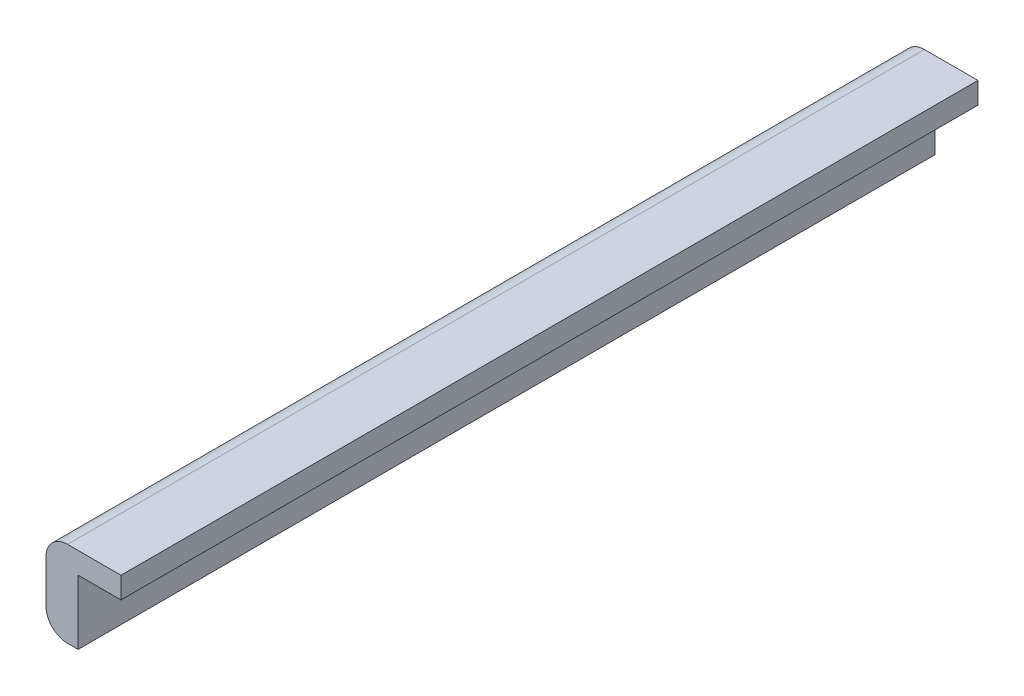
SolidWorks part; units mm, degrees
ref_plane "Front Plane" through (0, 0, 0) normal (0, 0, 1) x (1, 0, 0)
ref_plane "Top Plane" through (0, 0, 0) normal (0, 1, 0) x (1, 0, 0)
ref_plane "Right Plane" through (0, 0, 0) normal (1, 0, 0) x (0, 0, -1)
sketch "Sketch1" plane through (0, 0, 0) normal (0, 0, 1) x (1, 0, 0)
  line L0 (0, 0) -> (0, -62.0657) construction
  line L1 (0, 0) -> (0, -6)
  line L2 (0, -6) -> (-1, -6)
  line L3 (-3, -4) -> (-3, 0)
  line L9 (-1, 2) -> (4, 2)
  line L10 (4, 2) -> (4, 0)
  line L11 (4, 0) -> (0, 0)
  arc A5 (-3, 0) -> (-1, 2) centre (-1, 0) cw
  arc A6 (-1, -6) -> (-3, -4) centre (-1, -4) cw
  point P12 (-3, -6)
  dimension "D5" = 2
  dimension "D1" = 6
  dimension "D2" = 3
  dimension "D3" = 2
  dimension "D4" = 4
extrude "Boss-Extrude1" add sketch "Sketch1" along normal blind 80
